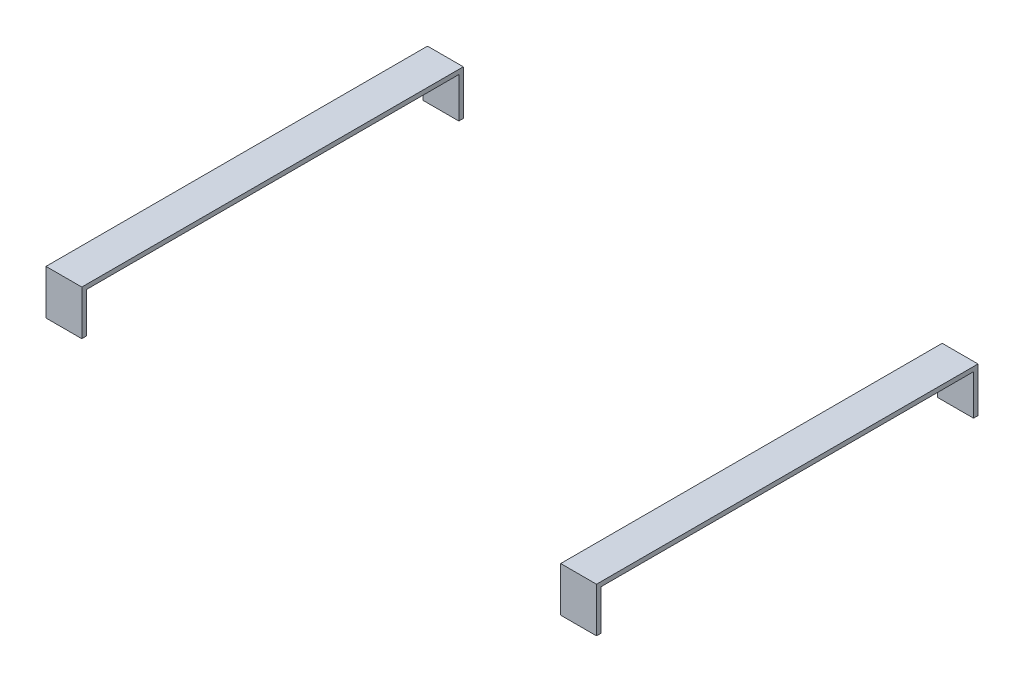
SolidWorks part; units mm, degrees
ref_plane "Alzado" through (0, 0, 0) normal (0, 0, 1) x (1, 0, 0)
ref_plane "Planta" through (0, 0, 0) normal (0, 1, 0) x (1, 0, 0)
ref_plane "Vista lateral" through (0, 0, 0) normal (1, 0, 0) x (0, 0, -1)
sketch "Croquis1" plane through (0, 0, 0) normal (0, 1, 0) x (1, 0, 0)
  line L0 (0, 0) -> (1070, 0) construction
  line L1 (0, 0) -> (-80, 0)
  line L2 (0, 0) -> (0, -10)
  line L3 (0, -10) -> (-80, -10)
  line L4 (-80, 0) -> (-80, -10)
  line L5 (-80, -10) -> (-80, -426.2) construction
  line L6 (1070, 0) -> (1150, 0)
  line L7 (1070, 0) -> (1070, -10)
  line L8 (1070, -10) -> (1150, -10)
  line L9 (1150, 0) -> (1150, -10)
  line L10 (-80, -426.2) -> (239.0685, -426.2) construction
  line L11 (0, -852.4) -> (1070, -852.4) construction
  line L12 (1150, -852.4) -> (1150, -842.4)
  line L13 (1070, -842.4) -> (1150, -842.4)
  line L14 (1070, -852.4) -> (1070, -842.4)
  line L15 (1070, -852.4) -> (1150, -852.4)
  line L16 (-80, -852.4) -> (-80, -842.4)
  line L17 (0, -842.4) -> (-80, -842.4)
  line L18 (0, -852.4) -> (0, -842.4)
  line L19 (0, -852.4) -> (-80, -852.4)
  dimension "D1" = 10
  dimension "D2" = 80
  dimension "D3" = 1070
  dimension "D4" = 80
  dimension "D5" = 10
  dimension "D6" = 416.2
extrude "Saliente-Extruir1" add sketch "Croquis1" along normal blind 100
sketch "Croquis2" plane through (0, 0, 10) normal (0, 0, 1) x (1, 0, 0)
  line L0 (0, 100) -> (0, 0) construction
  line L1 (-80, 100) -> (0, 100)
  line L2 (-80, 100) -> (-80, 90)
  line L3 (-80, 90) -> (0, 90)
  line L4 (0, 100) -> (0, 90)
  line L5 (1150, 100) -> (1150, 0) construction
  line L6 (1070, 100) -> (1150, 100)
  line L7 (1070, 100) -> (1070, 90)
  line L8 (1070, 90) -> (1150, 90)
  line L9 (1150, 100) -> (1150, 90)
  dimension "D1" = 10
  dimension "D2" = 10
extrude "Saliente-Extruir2" add sketch "Croquis2" along normal up to surface (832.4 mm away) up to face at (1110, 50, 842.4)
